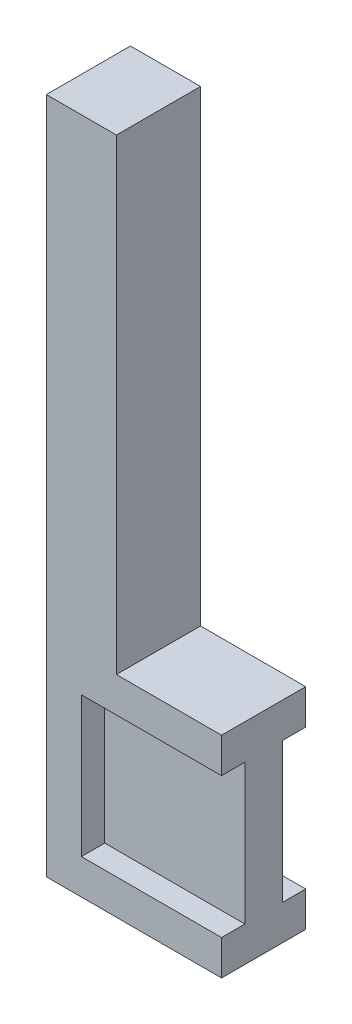
SolidWorks part; units mm, degrees
ref_plane "Plan de face" through (0, 0, 0) normal (0, 0, 1) x (1, 0, 0)
ref_plane "Plan de dessus" through (0, 0, 0) normal (0, 1, 0) x (1, 0, 0)
ref_plane "Plan de droite" through (0, 0, 0) normal (1, 0, 0) x (0, 0, -1)
sketch "Esquisse1" plane through (0, 0, 0) normal (0, 0, 1) x (1, 0, 0)
  line L13 (0, 0) -> (6, 0)
  line L14 (0, 0) -> (0, 6)
  line L15 (0, 6) -> (6, 6)
  line L16 (6, 0) -> (6, 6)
  dimension "D1" = 6
  dimension "D2" = 6
extrude "Boss.-Extru.3" add sketch "Esquisse1" along normal blind 1.6
sketch "Esquisse3" plane through (0, 0, 1.6) normal (0, 0, 1) x (1, 0, 0)
  line L1 (0, 6) -> (6, 6)
  line L2 (0, 6) -> (0, 7.5)
  line L3 (0, 7.5) -> (6, 7.5)
  line L4 (6, 6) -> (6, 7.5)
  line L5 (0, 0) -> (6, 0)
  line L6 (0, 0) -> (0, -1.5)
  line L7 (0, -1.5) -> (6, -1.5)
  line L8 (6, 0) -> (6, -1.5)
  line L9 (0, 7.5) -> (-1.5, 7.5)
  line L10 (0, 7.5) -> (0, -1.5)
  line L11 (0, -1.5) -> (-1.5, -1.5)
  line L12 (-1.5, 7.5) -> (-1.5, -1.5)
  line M6 (0, 6) -> (0, 0)
  line M7 (0, 0) -> (6, 0)
  line M9 (6, 6) -> (0, 6)
  dimension "D1" = 1.5
  dimension "D2" = 1.5
  dimension "D3" = 6
  dimension "D4" = 6
  dimension "D5" = 1.5
extrude "Boss.-Extru.4" add sketch "Esquisse3" along normal blind 1 and the other way blind 2.6 contours L4 L3 L2 M9 | L9 L12 L11 L6 L2 M6 | L8 L6 L7 M7
sketch "Esquisse6" plane through (0, 7.5, 0) normal (0, 1, 0) x (1, 0, 0)
  line L0 (-1.5, -2.6) -> (6, -2.6) construction
  line L1 (-1.5, 1) -> (1.5, 1)
  line L2 (-1.5, 1) -> (-1.5, -2.6)
  line L3 (-1.5, -2.6) -> (1.5, -2.6)
  line L4 (1.5, 1) -> (1.5, -2.6)
  dimension "D1" = 3
extrude "Boss.-Extru.7" add sketch "Esquisse6" along normal blind 20
